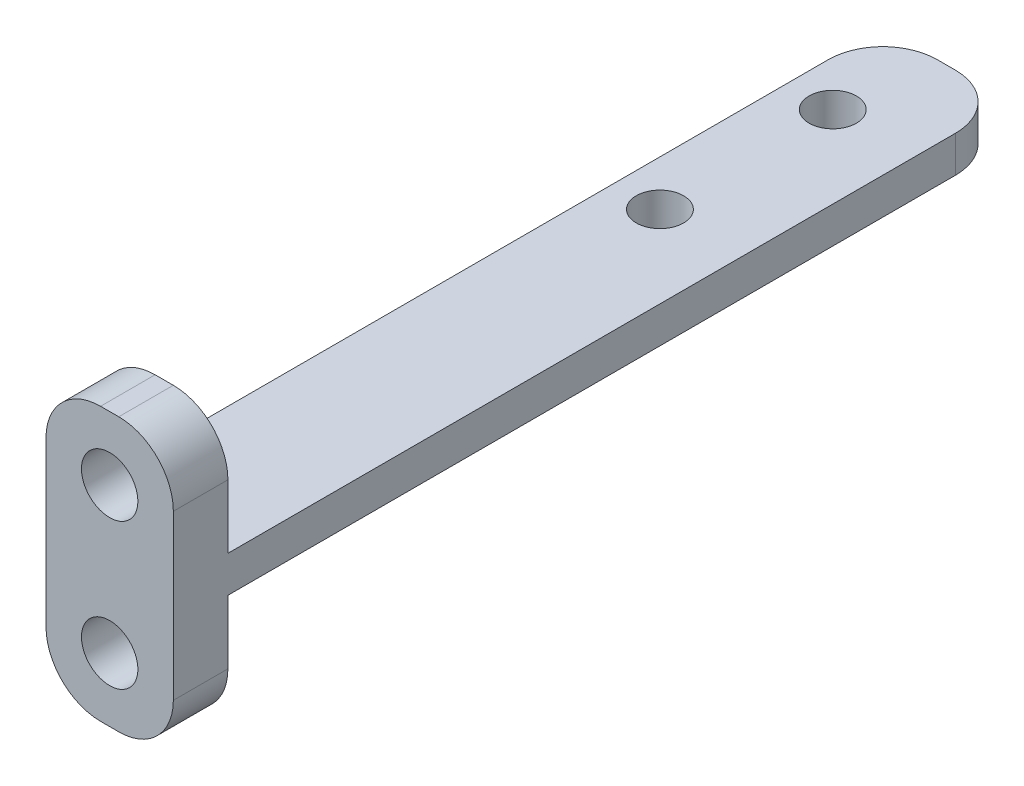
SolidWorks part; units mm, degrees
ref_plane "前视基准面" through (0, 0, 0) normal (0, 0, 1) x (1, 0, 0)
ref_plane "上视基准面" through (0, 0, 0) normal (0, 1, 0) x (1, 0, 0)
ref_plane "右视基准面" through (0, 0, 0) normal (1, 0, 0) x (0, 0, -1)
other "Configuration Table"
sketch "草图1" plane through (0, 0, 0) normal (0, 1, 0) x (1, 0, 0)
  line L0 (0, 11.5) -> (-50000, 11.5) construction
  line L1 (3.5, -21.5) -> (-3.5, -21.5)
  line L2 (3.5, -21.5) -> (3.5, 21.5)
  line L3 (3.5, 21.5) -> (-3.5, 21.5)
  line L4 (-3.5, -21.5) -> (-3.5, 21.5)
  line L5 (3.5, -21.5) -> (-3.5, 21.5) construction
  line L6 (3.5, 21.5) -> (-3.5, -21.5) construction
  circle A0 centre (-1, 16.25) radius 1.3
  circle A1 centre (-1, 6.75) radius 1.3
  point P0 (0, 0)
  point P12 (0, 0)
  dimension "D4" = 2.6
  dimension "D1" = 43
  dimension "D2" = 7
  dimension "D3" = 9.5
  dimension "D5" = 2.5
  dimension "D6" = 10
extrude "凸台-拉伸1" add sketch "草图1" along normal blind 2
sketch "草图2" plane through (0, 0, 0) normal (0, 1, 0) x (1, 0, 0)
  line L1 (3.5, -21.5) -> (-3.5, -21.5)
  line L2 (3.5, -21.5) -> (3.5, -24.5)
  line L3 (3.5, -24.5) -> (-3.5, -24.5)
  line L4 (-3.5, -21.5) -> (-3.5, -24.5)
  dimension "D1" = 3
  dimension "D2" = 7
extrude "凸台-拉伸2" add sketch "草图2" along normal blind 8.5 and the other way blind 6.5
sketch "草图3" plane through (0, 0, 0) normal (0, 0, 1) x (1, 0, 0)
  line L0 (-3.5, 1) -> (-50003.5, 1) construction
  line L1 (-3.5, -6.5) -> (-3.5, 8.5) construction
  line L2 (0, -5) -> (0, -50005) construction
  line L3 (-3.5, -6.5) -> (3.5, -6.5) construction
  line L4 (-3.5, 8.5) -> (3.5, 8.5) construction
  circle A0 centre (0, 5) radius 1.55
  circle A1 centre (0, -3) radius 1.55
  point P4 (-3.5, 1)
  point P9 (0, -6.5)
  dimension "D1" = 3.1
  dimension "D2" = 3.5
extrude "切除-拉伸1" cut sketch "草图3" along normal through all
fillet "圆角1" radius 3 2 edges at (-3.5, 1, -21.5) (3.5, 1, -21.5)
fillet "圆角2" radius 3 4 edges at (-3.5, -6.5, 23) (3.5, -6.5, 23) (-3.5, 8.5, 23) (3.5, 8.5, 23)
